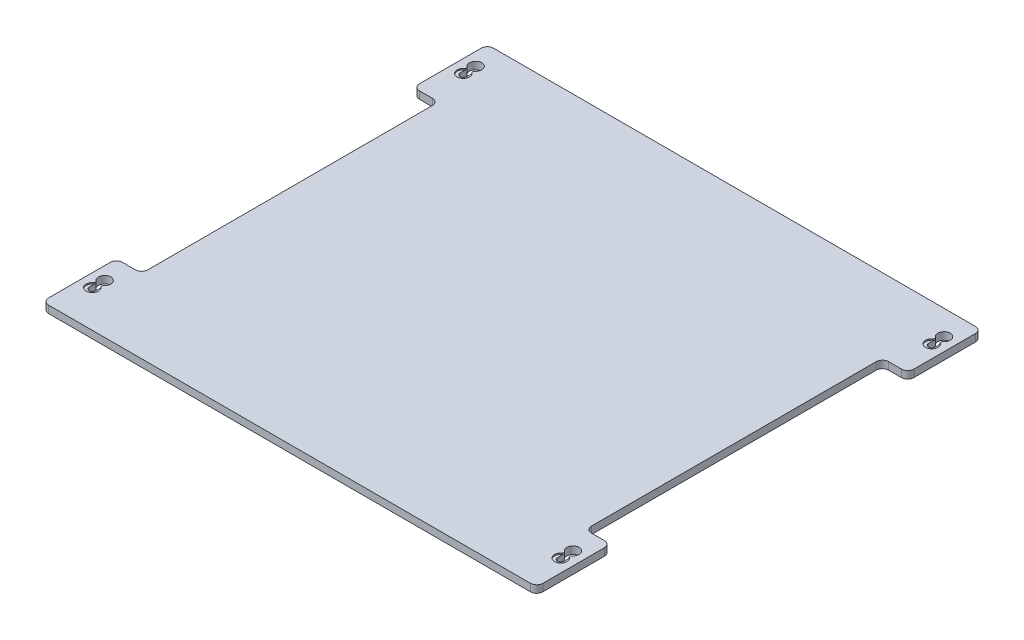
SolidWorks part; units mm, degrees
material "Acrylic (Medium-high impact)"
ref_plane "Front Plane" through (0, 0, 0) normal (0, 0, 1) x (1, 0, 0)
ref_plane "Top Plane" through (0, 0, 0) normal (0, 1, 0) x (1, 0, 0)
ref_plane "Right Plane" through (0, 0, 0) normal (1, 0, 0) x (0, 0, -1)
sketch "Sketch1" plane through (0, 0, 0) normal (0, 1, 0) x (1, 0, 0)
  line L0 (0, -180.5) -> (200.5, -180.5)
  line L1 (200.5, -180.5) -> (200.5, -120.5)
  line L2 (200.5, -120.5) -> (180, -120.5)
  line L3 (180, -120.5) -> (180, 0)
  line L4 (180, 0) -> (180, 120.5)
  line L5 (180, 120.5) -> (200.5, 120.5)
  line L6 (200.5, 120.5) -> (200.5, 180.5)
  line L7 (200.5, 180.5) -> (0, 180.5)
  line L8 (0, 180.5) -> (-200.5, 180.5)
  line L9 (-200.5, 180.5) -> (-200.5, 120.5)
  line L10 (-200.5, 120.5) -> (-180, 120.5)
  line L11 (-180, 120.5) -> (-180, 0)
  line L12 (-180, 0) -> (-180, -120.5)
  line L13 (-180, -120.5) -> (-200.5, -120.5)
  line L14 (-200.5, -120.5) -> (-200.5, -180.5)
  line L15 (-200.5, -180.5) -> (0, -180.5)
  line L16 (-180, 0) -> (0, 0) construction
  line L17 (0, 0) -> (0, -180.5) construction
  line L18 (180, 0) -> (0, 0) construction
  line L19 (0, 0) -> (0, 180.5) construction
  dimension "D1" = 361
  dimension "D2" = 360
  dimension "D3" = 60
  dimension "D4" = 401
extrude "Boss-Extrude1" add sketch "Sketch1" along normal blind 6
sketch "Sketch2" plane through (0, 6, 0) normal (0, 1, 0) x (1, 0, 0)
  line L0 (190, -120.5) -> (190, -180.5) construction
  line L3 (187.4, -150.5) -> (187.4, -144.7708)
  line L4 (187.4, 150.5) -> (187.4, 156.2292)
  line L5 (192.6, -144.7708) -> (192.6, -150.5)
  line L6 (192.6, 156.2292) -> (192.6, 150.5)
  line L7 (190, 120.5) -> (190, 180.5) construction
  line L9 (200.5, 180.5) -> (-200.5, 180.5) construction
  line L10 (-200.5, -180.5) -> (200.5, -180.5) construction
  line L13 (200.5, -120.5) -> (180, -120.5) construction
  line L16 (180, 120.5) -> (200.5, 120.5) construction
  line L17 (0, 0) -> (0, 180.5) construction
  arc A0 (187.4, -150.5) -> (192.6, -150.5) centre (190, -150.5) ccw
  arc A1 (192.6, -144.7708) -> (187.4, -144.7708) centre (190, -140.5) ccw
  arc A2 (187.4, 150.5) -> (192.6, 150.5) centre (190, 150.5) ccw
  arc A3 (192.6, 156.2292) -> (187.4, 156.2292) centre (190, 160.5) ccw
  dimension "D1" = 10
  dimension "D2" = 2.6
  dimension "D3" = 5
  dimension "D5" = 2.6
  dimension "D6" = 5
  dimension "D4" = 10
  dimension "D7" = 380
extrude "Cut-Extrude1" cut sketch "Sketch2" against normal through all
sketch "Sketch3" plane through (0, 6, 0) normal (0, 1, 0) x (1, 0, 0)
  circle A0 centre (190, 150.5) radius 5
  circle A1 centre (190, -150.5) radius 5
  dimension "D1" = 10
extrude "Cut-Extrude2" cut sketch "Sketch3" against normal blind 1
mirror "Mirror1" about plane through (0, 0, 0) normal (1, 0, 0) of "Cut-Extrude2", "Cut-Extrude1"
fillet "Fillet1" radius 5 12 edges at (-180, 3, 120.5) (-200.5, 3, 120.5) (-200.5, 3, 180.5) (-180, 3, -120.5) (-200.5, 3, -120.5) (-200.5, 3, -180.5) (180, 3, -120.5) (200.5, 3, -120.5) (200.5, 3, -180.5) (200.5, 3, 120.5) (180, 3, 120.5) (200.5, 3, 180.5)
